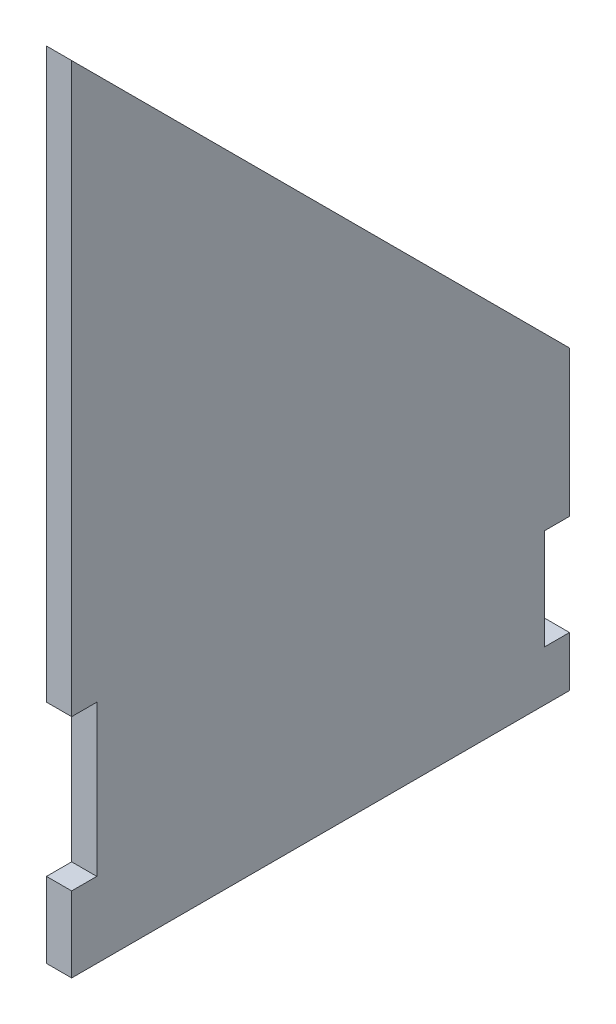
SolidWorks part; units mm, degrees
ref_plane "정면" through (0, 0, 0) normal (0, 0, 1) x (1, 0, 0)
ref_plane "윗면" through (0, 0, 0) normal (0, 1, 0) x (1, 0, 0)
ref_plane "우측면" through (0, 0, 0) normal (1, 0, 0) x (0, 0, -1)
sketch "스케치1" plane through (0, 0, 0) normal (1, 0, 0) x (0, 0, -1)
  line L1 (0, 0) -> (98.9949, 0)
  line L2 (0, 0) -> (0, 157.9949)
  line L3 (0, 157.9949) -> (98.9949, 59)
  line L4 (98.9949, 0) -> (98.9949, 59)
  dimension "D1" = 135
  dimension "D2" = 140
  dimension "D3" = 59
extrude "보스-돌출1" add sketch "스케치1" along normal blind 5
sketch "스케치3" plane through (5, 0, 0) normal (1, 0, 0) x (0, 0, -1)
  line L0 (5, 45) -> (5, 15) construction
  line L1 (5, 45) -> (0, 45)
  line L2 (5, 45) -> (5, 15)
  line L3 (5, 15) -> (0, 15)
  line L4 (0, 45) -> (0, 15)
  line L5 (0, 157.9949) -> (0, 0) construction
  line L6 (0, 60) -> (5, 60) construction
  line L7 (0, 0) -> (98.9949, 0) construction
  line L8 (93.9949, 10) -> (93.9949, 30) construction
  line L9 (93.9949, 30) -> (98.9949, 30)
  line L10 (93.9949, 30) -> (93.9949, 10)
  line L11 (93.9949, 10) -> (98.9949, 10)
  line L12 (98.9949, 30) -> (98.9949, 10)
  line L13 (98.9949, 0) -> (98.9949, 59) construction
  line L14 (98.9949, 40) -> (93.9949, 40) construction
  dimension "D1" = 15
  dimension "D2" = 15
  dimension "D3" = 10
  dimension "D4" = 10
extrude "컷-돌출2" cut sketch "스케치3" against normal blind 10
